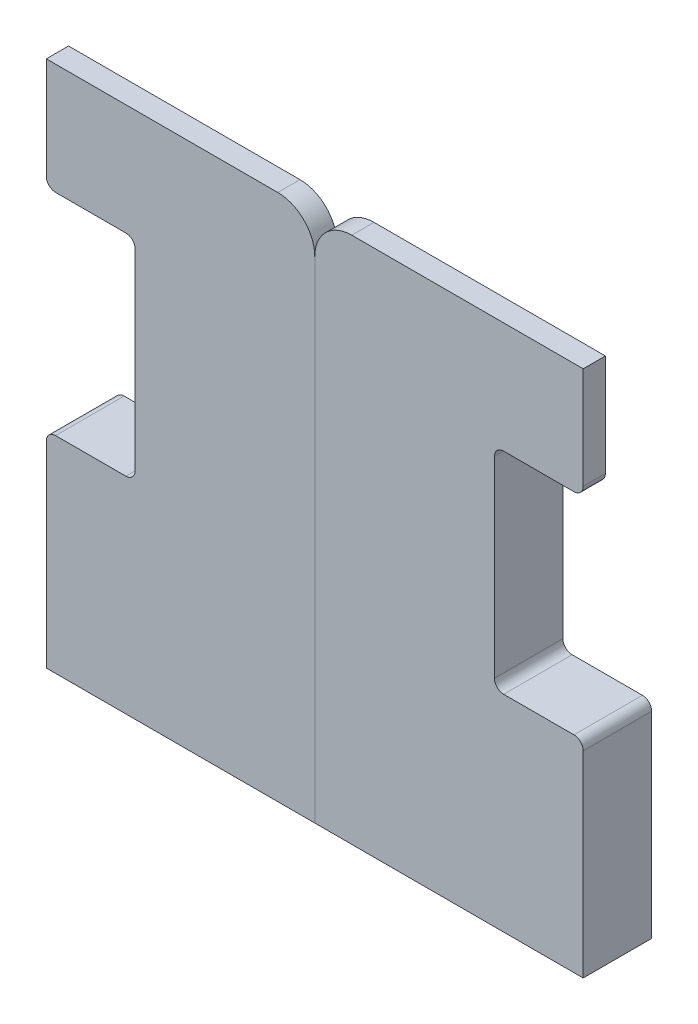
SolidWorks part; units mm, degrees
ref_plane "Front Plane" through (0, 0, 0) normal (0, 0, 1) x (1, 0, 0)
ref_plane "Top Plane" through (0, 0, 0) normal (0, 1, 0) x (1, 0, 0)
ref_plane "Right Plane" through (0, 0, 0) normal (1, 0, 0) x (0, 0, -1)
sketch "Sketch1" plane through (0, 0, 0) normal (0, 0, 1) x (1, 0, 0)
  line L1 (-8.5, 22.5) -> (8.5, 22.5)
  line L2 (-8.5, 22.5) -> (-8.5, -22.5)
  line L3 (-8.5, -22.5) -> (8.5, -22.5)
  line L4 (8.5, 22.5) -> (8.5, -22.5)
  line L5 (-8.5, 22.5) -> (8.5, -22.5) construction
  line L6 (-8.5, -22.5) -> (8.5, 22.5) construction
  point P0 (0, 0)
  dimension "D1" = 17
  dimension "D2" = 45
extrude "Boss-Extrude1" add sketch "Sketch1" along normal blind 12
sketch "Sketch2" plane through (0, 0, 12) normal (0, 0, 1) x (1, 0, 0)
  line L0 (-8.5, -22.5) -> (-8.5, 22.5)
  line L1 (-8.5, 22.5) -> (8.5, 22.5)
  line L2 (8.5, 22.5) -> (8.5, 34.5)
  line L3 (8.5, 34.5) -> (-20.5, 34.5)
  line L4 (-20.5, 34.5) -> (-20.5, -22.5)
  line L5 (-20.5, -22.5) -> (-8.5, -22.5)
  dimension "D1" = 12
  dimension "D2" = 12
extrude "Boss-Extrude2" add sketch "Sketch2" against normal blind 7
fillet "Fillet1" radius 4 1 edges at (-20.5, 34.5, 8.5)
sketch "Sketch3" plane through (0, 0, 0) normal (0, 0, -1) x (-1, 0, 0)
  line L1 (-2.5, -0.25) -> (1.0917, -0.25)
  line L3 (-8.5, 34.5) -> (16.5, 34.5) construction
  line L4 (-2.5, 34.5) -> (1.0917, 34.5)
  line L5 (1.0917, 22.5) -> (1.0917, -0.25)
  line L6 (1.0917, 22.5) -> (-8.5, 22.5)
  line L7 (-2.5, 34.5) -> (-3.5, 34.5)
  line L9 (-2.5, -0.25) -> (-3.5, -0.25)
  line L12 (-8.5, 22.5) -> (-8.5, -0.25)
  line L13 (-8.5, -22.5) -> (-8.5, 22.5) construction
  line L14 (-8.5, -0.25) -> (-3.5, -0.25)
  line L17 (-8.5, 22.5) -> (8.5, 22.5) construction
extrude "Cut-Extrude1" cut sketch "Sketch3" against normal through all
sketch "Sketch4" plane through (0, 0, 12) normal (0, 0, 1) x (1, 0, 0)
  line L0 (8.5, 34.5) -> (22.6833, 34.5)
  line L1 (8.5, 22.5) -> (8.5, -0.25)
  line L7 (-1.0917, 22.5) -> (8.5, 22.5)
  line L9 (8.5, -0.25) -> (-1.0917, -0.25)
  line L10 (8.5, 34.5) -> (-16.5, 34.5)
  line L11 (-20.5, 30.5) -> (-20.5, -22.5)
  line L12 (-20.5, -22.5) -> (8.5, -22.5)
  line L13 (8.5, -22.5) -> (8.5, -0.25)
  line L14 (-1.0917, -0.25) -> (-1.0917, 22.5)
  line L18 (8.5, 34.5) -> (-16.5, 34.5)
  line L19 (-20.5, 30.5) -> (-20.5, -22.5)
  line L20 (-20.5, -22.5) -> (8.5, -22.5)
  line L21 (8.5, -22.5) -> (8.5, -0.25)
  line L25 (8.5, 22.5) -> (8.5, 34.5)
  line L26 (8.5, 22.5) -> (8.5, 34.5)
  arc A1 (-16.5, 34.5) -> (-20.5, 30.5) centre (-16.5, 30.5) ccw
  arc A2 (-16.5, 34.5) -> (-20.5, 30.5) centre (-16.5, 30.5) ccw
  line M10 (8.5, -0.25) -> (-1.0917, -0.25)
  line M11 (-1.0917, -0.25) -> (-1.0917, 22.5)
  line M12 (8.5, 34.5) -> (-16.5, 34.5)
  arc M13 (-16.5, 34.5) -> (-20.5, 30.5) centre (-16.5, 30.5) ccw
  line M14 (-20.5, 30.5) -> (-20.5, -22.5)
  line M15 (-20.5, -22.5) -> (8.5, -22.5)
  line M16 (8.5, -22.5) -> (8.5, -0.25)
  line M20 (-1.0917, 22.5) -> (8.5, 22.5)
  line M31 (8.5, 22.5) -> (8.5, 34.5)
  dimension "D1" = 0
extrude "Cut-Extrude2" cut sketch "Sketch4" against normal offset from surface (4.6 mm away) 2.4 contours M11 M20 M31 M12 M13 M14 M15 M16 M10 up to face at (-7.4275, 15.3536, 5)
sketch "Sketch5" plane through (0, 0, 0) normal (0, 0, -1) x (-1, 0, 0)
  line L1 (8.5, 22.5) -> (5, 22.5)
  line L2 (8.5, 22.5) -> (8.5, 19)
  line L3 (8.5, 19) -> (5, 19)
  line L4 (5, 22.5) -> (5, 19)
  dimension "D1" = 3.5
fillet "Fillet2" radius 1 4 edges at (8.5, -0.25, 3.7) (-1.0917, -0.25, 3.7) (8.5, 22.5, 6.2) (-1.0917, 22.5, 6.2)
fillet "Fillet3" radius 1 3 edges at (-8.5, -22.5, 2.5) (-1.0917, 22.5, 2.5) (-8.5, 22.5, 2.5)
mirror "Mirror1" about plane through (-20.5, 34.5, 5) normal (-1, 0, 0) of bodies 104
